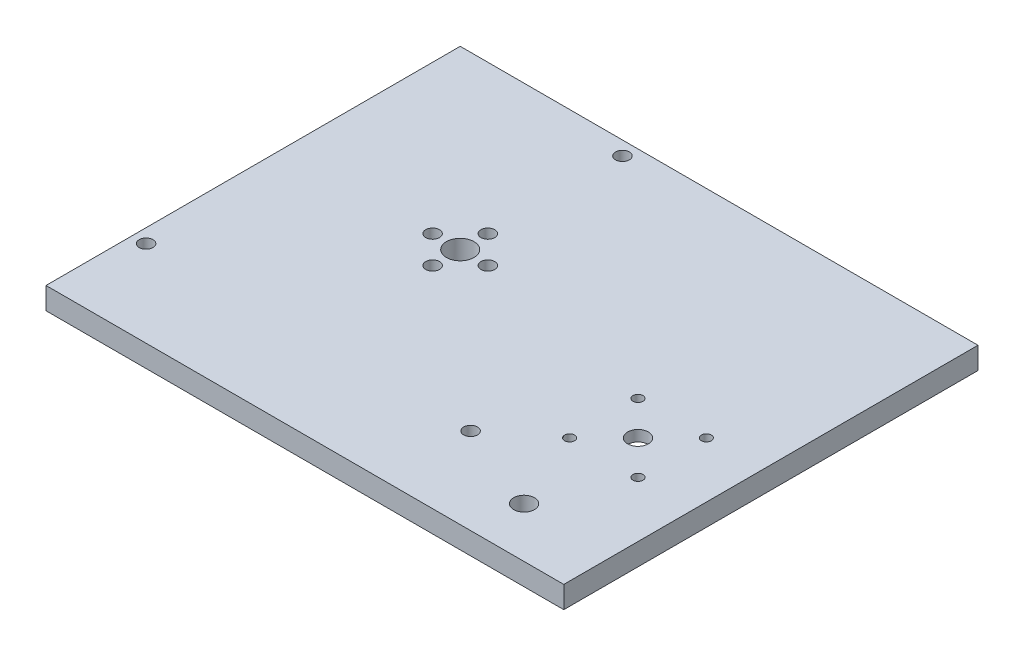
SolidWorks part; units mm, degrees
ref_plane "Front Plane" through (0, 0, 0) normal (0, 0, 1) x (1, 0, 0)
ref_plane "Top Plane" through (0, 0, 0) normal (0, 1, 0) x (1, 0, 0)
ref_plane "Right Plane" through (0, 0, 0) normal (1, 0, 0) x (0, 0, -1)
sketch "Sketch1" plane through (0, 0, 0) normal (0, 1, 0) x (1, 0, 0)
  line L1 (0, 0) -> (150, 0)
  line L2 (0, 0) -> (0, 120)
  line L3 (0, 120) -> (150, 120)
  line L4 (150, 0) -> (150, 120)
  dimension "D1" = 150
  dimension "D2" = 120
extrude "Boss-Extrude1" add sketch "Sketch1" along normal blind 6.35
sketch "Sketch2" plane through (0, 6.35, 0) normal (0, 1, 0) x (1, 0, 0)
  line L0 (94, 31) -> (150, 31)
  line L1 (150, 0) -> (150, 120) construction
  line L2 (94, 31) -> (94, 0)
  line L3 (0, 0) -> (150, 0) construction
  line L4 (94, 31) -> (94, 120)
  line L5 (150, 120) -> (0, 120) construction
  line L6 (124, 31) -> (124, 120)
  line L7 (124, 31) -> (124, 0)
  line L8 (94, 47.5) -> (124, 47.5)
  line L9 (94, 14.5) -> (124, 14.5)
  circle A0 centre (51, 116) radius 2
  circle A1 centre (4, 25) radius 2
  circle A2 centre (98, 25) radius 2
  circle A3 centre (124, 47.5) radius 3
  circle A4 centre (124, 14.5) radius 3
  circle A5 centre (51, 77) radius 2
  circle A6 centre (43, 69) radius 2
  circle A7 centre (51, 69) radius 4
  circle A8 centre (51, 61) radius 2
  circle A9 centre (59, 69) radius 2
  dimension "D4" = 6
  dimension "D5" = 6
  dimension "D1" = 30
  dimension "D2" = 16.5
  dimension "D3" = 16.5
extrude "Cut-Extrude1" cut sketch "Sketch2" against normal blind 10 contours A0 | A1 | A2 | L7 A4 | L7 A4 L9 | L9 A4 L7 | L8 A3 L6 | L6 A3 L8 | L6 A3 | A5 | A6 | A7 | A9 | A8
sketch "Sketch3" plane through (0, 0, 0) normal (0, -1, 0) x (1, 0, 0)
  circle A0 centre (124, -47.5) radius 11
  dimension "D1" = 22
extrude "Cut-Extrude2" cut sketch "Sketch3" against normal blind 3.21
sketch "Sketch4" plane through (0, 6.35, 0) normal (0, 1, 0) x (1, 0, 0)
  circle A22 centre (133.8995, 57.3995) radius 1.45
  circle A23 centre (133.8995, 57.3995) radius 1.45
  circle A25 centre (114.1005, 57.3995) radius 1.45
  circle A26 centre (114.1005, 57.3995) radius 1.45
  circle A28 centre (114.1005, 37.6005) radius 1.45
  circle A29 centre (114.1005, 37.6005) radius 1.45
  circle A31 centre (133.8995, 37.6005) radius 1.45
  circle A32 centre (133.8995, 37.6005) radius 1.45
  dimension "D1" = 0.2
  dimension "D2" = 0.2
  dimension "D3" = 0.2
  dimension "D4" = 0.2
extrude "Cut-Extrude3" cut sketch "Sketch4" against normal blind 6.35 contours A23 | A29 | A32 | A26
